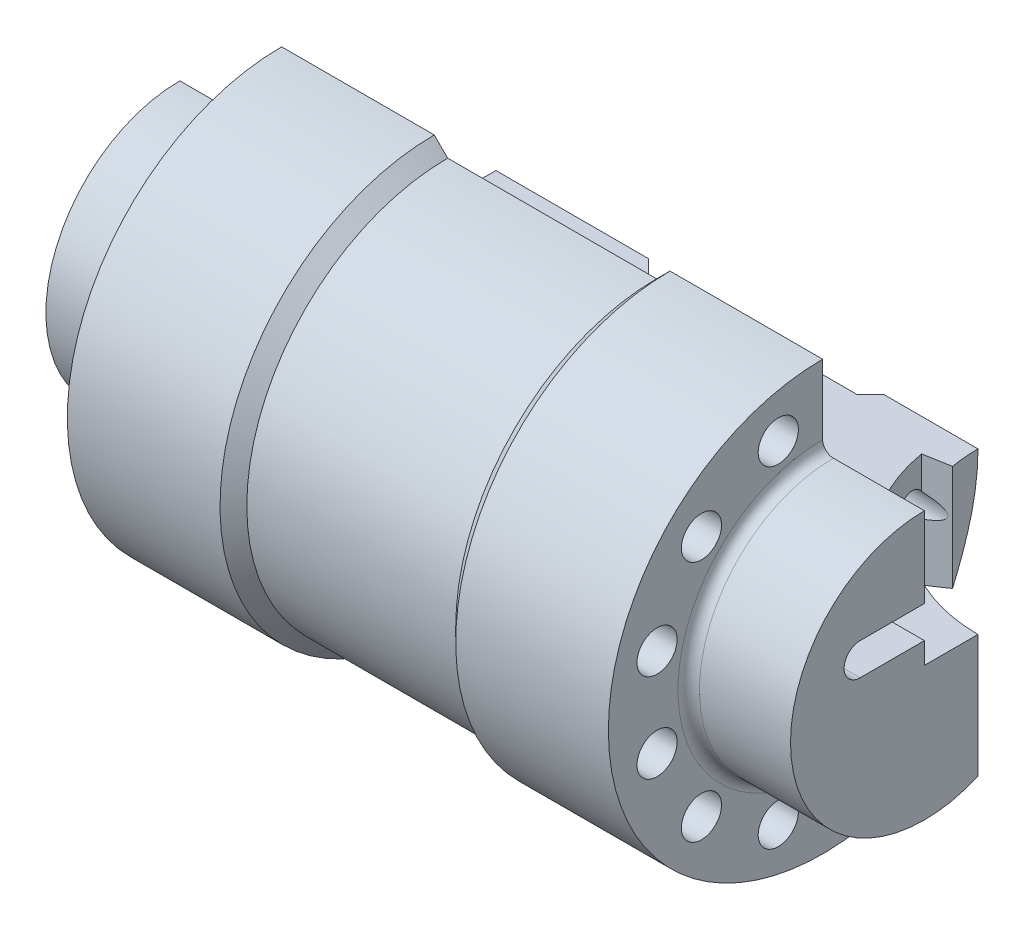
SolidWorks part; units mm, degrees
material "AISI 1020"
ref_plane "Front Plane" through (0, 0, 0) normal (0, 0, 1) x (1, 0, 0)
ref_plane "Top Plane" through (0, 0, 0) normal (0, 1, 0) x (1, 0, 0)
ref_plane "Right Plane" through (0, 0, 0) normal (1, 0, 0) x (0, 0, -1)
sketch "Sketch1" plane through (0, 0, 0) normal (0, 0, 1) x (1, 0, 0)
  line L0 (47.5, 40) -> (50, 37.5)
  line L1 (0, 0) -> (139, 0)
  line L2 (0, 0) -> (0, 25)
  line L3 (19, 40) -> (47.5, 40)
  line L4 (139, 0) -> (139, 25)
  line L7 (0, 25) -> (17, 25)
  line L8 (19, 40) -> (19, 27)
  line L11 (139, 25) -> (122, 25)
  line L12 (120, 40) -> (120, 27)
  line L15 (50, 37.5) -> (89, 37.5)
  line L17 (91.5, 40) -> (89, 37.5)
  line L18 (91.5, 40) -> (120, 40)
  arc A0 (17, 25) -> (19, 27) centre (17, 27) ccw
  arc A1 (122, 25) -> (120, 27) centre (122, 27) cw
  dimension "D9" = 2
  dimension "D10" = 2
  dimension "D1" = 19
  dimension "D2" = 19
  dimension "D3" = 139
  dimension "D4" = 28.5
  dimension "D5" = 28.5
  dimension "D6" = 2.5
  dimension "D7" = 45
  dimension "D8" = 45
  dimension "D11" = 25
  dimension "D12" = 25
  dimension "D13" = 15
revolve "Revolve1" add sketch "Sketch1" angle 270 about L1
sketch "Sketch2" plane through (0, 0, 0) normal (-1, 0, 0) x (0, 0, 1)
  line L0 (0, 7) -> (12, 7) construction
  line L1 (0, 25) -> (0, 0) construction
  line L2 (0, 10) -> (12, 10)
  line L3 (0, 4) -> (12, 4)
  arc A0 (0, 10) -> (0, 4) centre (0, 7) ccw
  arc A1 (12, 4) -> (12, 10) centre (12, 7) ccw
  point P4 (6, 7)
  dimension "D3" = 3
  dimension "D1" = 7
  dimension "D2" = 12
extrude "Cut-Extrude1" cut sketch "Sketch2" against normal through all
sketch "Sketch3" plane through (120, 0, 0) normal (1, 0, 0) x (0, 0, -1)
  line L0 (0, 0) -> (-10.3528, 38.637) construction
  line L1 (0, 27) -> (0, 40) construction
  arc A0 (-4.6093, 31.6663) -> (31.6663, -4.6093) centre (0, 0) ccw
  arc A1 (0, 40) -> (40, 0) centre (0, 0) ccw construction
  circle A2 centre (-8.2822, 30.9096) radius 3.75
  circle A6 centre (30.9096, -8.2822) radius 3.75
  circle A7 centre (22.6274, -22.6274) radius 3.75
  circle A8 centre (8.2822, -30.9096) radius 3.75
  circle A9 centre (-8.2822, -30.9096) radius 3.75
  circle A10 centre (-22.6274, -22.6274) radius 3.75
  circle A11 centre (-30.9096, -8.2822) radius 3.75
  circle A12 centre (-30.9096, 8.2822) radius 3.75
  circle A13 centre (-22.6274, 22.6274) radius 3.75
  arc A14 (4.6093, 31.6663) -> (11.8413, 29.7285) centre (8.2822, 30.9096) ccw [skipped]
  arc A15 (25.1191, 19.825) -> (19.825, 25.1191) centre (22.6274, 22.6274) ccw [skipped]
  arc A16 (29.7285, 11.8413) -> (31.6663, 4.6093) centre (30.9096, 8.2822) ccw [skipped]
  point P35 (0, 0)
  dimension "D1" = 64
  dimension "D3" = 7.5
  dimension "D2" = 15
  dimension "D4" = 12
extrude "Cut-Extrude2" cut sketch "Sketch3" against normal through all contours A2 | A13 | A12 | A11 | A10 | A9 | A8 | A7 | A6
sketch "Sketch5" plane through (0, 0, 0) normal (0, 1, 0) x (1, 0, 0)
  line L1 (139, 25) -> (120, 25) construction
  line L2 (139, 25) -> (139, 40) construction
  line L3 (139, 40) -> (120, 40) construction
  line L4 (120, 25) -> (120, 40) construction
  circle A1 centre (139, 40) radius 30
  dimension "D2" = 60
extrude "Cut-Extrude3" cut sketch "Sketch5" against normal through all
sketch "Sketch6" plane through (0, 0, 0) normal (0, 1, 0) x (1, 0, 0)
  line L5 (104.5317, 33.9223) -> (109.4558, 34.7906)
  line L6 (126.3215, 12.8108) -> (124.2084, 8.2792)
  arc A0 (109, 40) -> (139, 10) centre (139, 40) ccw construction
  arc A1 (104.5317, 33.9223) -> (124.2084, 8.2792) centre (139, 40) ccw
  arc A2 (109.4558, 34.7906) -> (126.3215, 12.8108) centre (139, 40) ccw
  dimension "D1" = 70
extrude "Cut-Extrude4" cut sketch "Sketch6" against normal through all
sketch "Sketch8" plane through (0, 0, 0) normal (-1, 0, 0) x (0, 0, 1)
  line L0 (-19.3649, -4) -> (-0.4005, -4)
  line L1 (-0.4005, -4) -> (3, -4)
  line L2 (4, -3) -> (4, -0.9037)
  line L3 (5, 0.0963) -> (19.9796, 0.0963)
  line L4 (-25, 0) -> (0, 0) construction
  line L5 (0, 4) -> (0, 0) construction
  arc A0 (-20.3332, -5.25) -> (20.9786, -0.9489) centre (0, 0) ccw
  arc A1 (-25, 0) -> (0, 25) centre (0, 0) ccw construction
  arc A2 (-20.3332, -5.25) -> (-19.3649, -4) centre (-19.3649, -5) cw
  arc A3 (3, -4) -> (4, -3) centre (3, -3) ccw
  arc A4 (4, -0.9037) -> (5, 0.0963) centre (5, -0.9037) cw
  arc A5 (19.9796, 0.0963) -> (20.9786, -0.9489) centre (19.9796, -0.9037) cw
  dimension "D1" = 4
  dimension "D4" = 1
  dimension "D5" = 1
  dimension "D6" = 1
  dimension "D7" = 1
  dimension "D2" = 4
  dimension "D3" = 4
extrude "Cut-Extrude5" cut sketch "Sketch8" against normal blind 10 contours L0 L1 A3 L2 A4 L3 A5 A0 A2
equation "\"A\"= 139.00"
equation "\"B\"= 19.00"
equation "\"C\"= 28.50"
